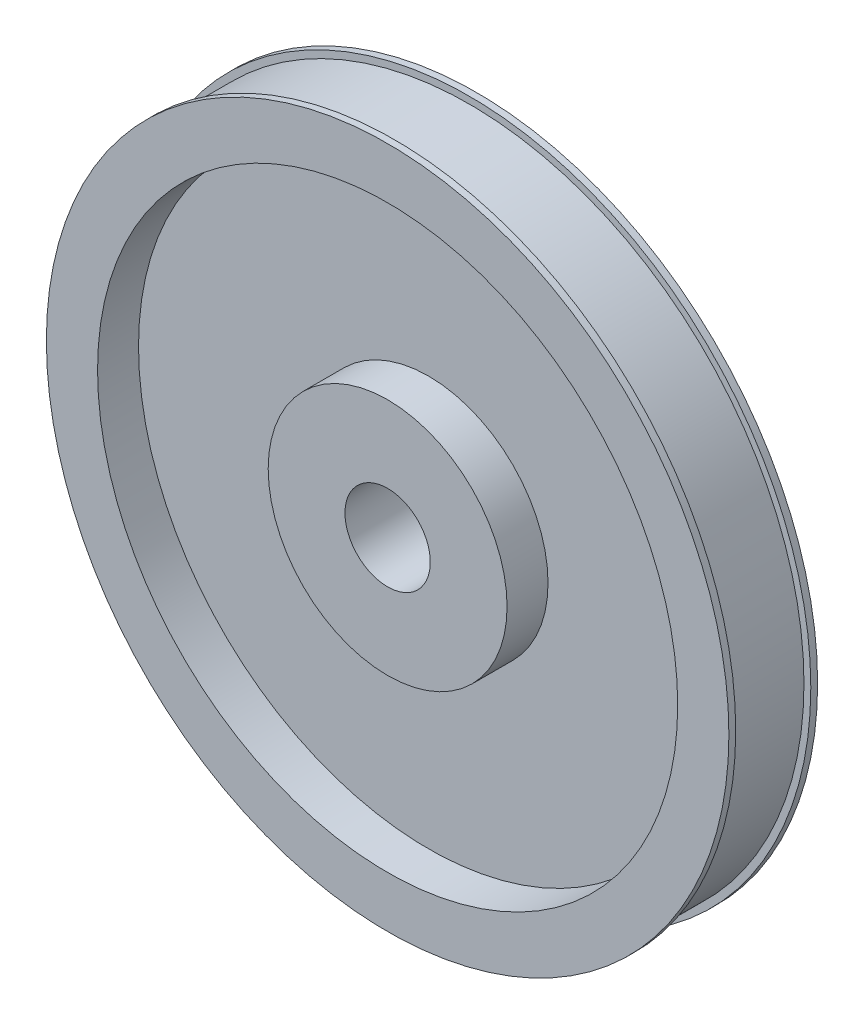
SolidWorks part; units mm, degrees
ref_plane "Front Plane" through (0, 0, 0) normal (0, 0, 1) x (1, 0, 0)
ref_plane "Top Plane" through (0, 0, 0) normal (0, 1, 0) x (1, 0, 0)
ref_plane "Right Plane" through (0, 0, 0) normal (1, 0, 0) x (0, 0, -1)
sketch "Sketch1" plane through (0, 0, 0) normal (0, 0, 1) x (1, 0, 0)
  circle A1 centre (0, 0) radius 12.5
  circle A2 centre (0, 0) radius 100
extrude "Boss-Extrude1" add sketch "Sketch1" along normal blind 26
sketch "Sketch3" plane through (0, 0, 26) normal (0, 0, 1) x (1, 0, 0)
  circle A0 centre (0, 0) radius 98
extrude "Cut-Extrude3" cut sketch "Sketch3" against normal blind 24 flip side to cut
sketch "Sketch6" plane through (0, 0, 26) normal (0, 0, 1) x (1, 0, 0)
  circle A0 centre (0, 0) radius 100
extrude "Boss-Extrude3" add sketch "Sketch6" against normal blind 2
sketch "Sketch7" plane through (0, 0, 0) normal (0, 0, -1) x (-1, 0, 0)
  circle A0 centre (0, 0) radius 12.5
extrude "Cut-Extrude6" cut sketch "Sketch7" against normal through all
sketch "Sketch8" plane through (0, 0, 26) normal (0, 0, 1) x (1, 0, 0)
  circle A0 centre (0, 0) radius 35
  circle A1 centre (0, 0) radius 85
extrude "Cut-Extrude7" cut sketch "Sketch8" against normal blind 12
